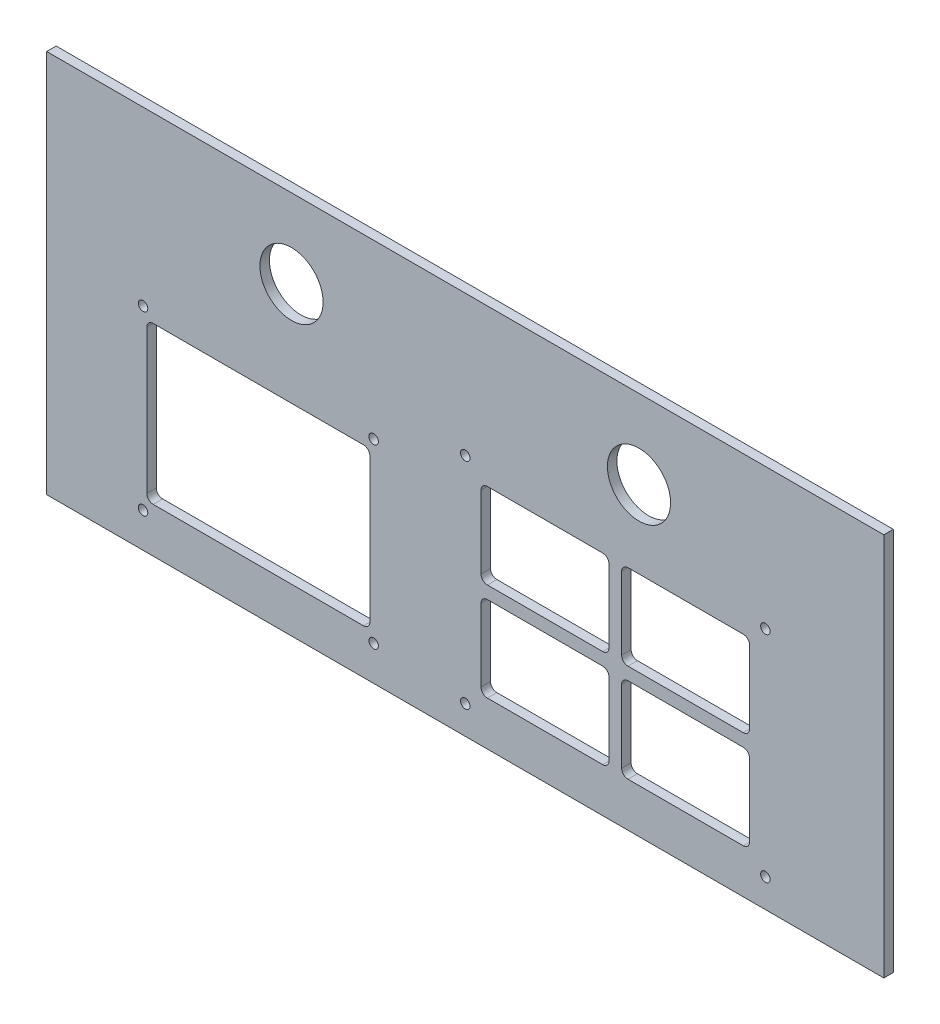
SolidWorks part; units mm, degrees
material "Thornel Mat VMA"
ref_plane "前视基准面" through (0, 0, 0) normal (0, 0, 1) x (1, 0, 0)
ref_plane "上视基准面" through (0, 0, 0) normal (0, 1, 0) x (1, 0, 0)
ref_plane "右视基准面" through (0, 0, 0) normal (1, 0, 0) x (0, 0, -1)
sketch "草图1" plane through (0, 0, 0) normal (0, 0, 1) x (1, 0, 0)
  line L1 (-132.5, -60.75) -> (132.5, -60.75)
  line L2 (-132.5, -60.75) -> (-132.5, 60.75)
  line L3 (-132.5, 60.75) -> (132.5, 60.75)
  line L4 (132.5, -60.75) -> (132.5, 60.75)
  line L5 (0, 60.75) -> (0, -60.75) construction
  line L6 (-132.5, 0) -> (132.5, 0) construction
  point P0 (0, 0)
  dimension "D1" = 265
  dimension "D2" = 121.5
extrude "凸台-拉伸1" add sketch "草图1" along normal blind 3
sketch "草图2" plane through (0, 0, 0) normal (0, 0, -1) x (-1, 0, 0)
  line L0 (50, 40.75) -> (60, 30.75) construction
  line L4 (60, 40.75) -> (50, 40.75)
  line L5 (50, 40.75) -> (50, 30.75)
  line L6 (50, 30.75) -> (60, 30.75)
  line L7 (60, 30.75) -> (60, 40.75)
  line L8 (60, 40.75) -> (50, 40.75) construction
  line L9 (50, 40.75) -> (50, 30.75) construction
  line L10 (50, 30.75) -> (60, 30.75) construction
  line L11 (60, 30.75) -> (60, 40.75) construction
  circle A0 centre (55, 35.75) radius 10
  dimension "D2" = 20
  dimension "D1" = 0
extrude "切除-拉伸1" cut sketch "草图2" against normal blind 10
mirror "镜向1" about plane through (0, 0, 0) normal (1, 0, 0) of "切除-拉伸1"
sketch "草图3" plane through (0, 0, 3) normal (0, 0, 1) x (1, 0, 0)
  line L0 (-97, -0.75) -> (-34, -42.75) construction
  line L2 (-100.8, -46.55) -> (-30.2, -46.55)
  line L3 (-100.8, -46.55) -> (-100.8, 3.05)
  line L4 (-100.8, 3.05) -> (-30.2, 3.05)
  line L5 (-30.2, -46.55) -> (-30.2, 3.05)
  line L6 (-65.5, 3.05) -> (-65.5, -46.55) construction
  line L7 (-100.8, -21.75) -> (-30.2, -21.75) construction
  line L40 (-97, -45.55) -> (-34, -45.55)
  line L41 (-31.2, -42.75) -> (-31.2, -37.25)
  line L42 (-31.2, -37.25) -> (-98, -37.25)
  line L43 (-98, -37.25) -> (-98, -36.25)
  line L44 (-98, -36.25) -> (-31.2, -36.25)
  line L45 (-31.2, -36.25) -> (-31.2, -34.25)
  line L46 (-31.2, -34.25) -> (-98, -34.25)
  line L47 (-98, -34.25) -> (-98, -33.25)
  line L48 (-98, -33.25) -> (-31.2, -33.25)
  line L49 (-31.2, -33.25) -> (-31.2, -28.25)
  line L50 (-31.2, -28.25) -> (-98, -28.25)
  line L51 (-98, -28.25) -> (-98, -27.25)
  line L52 (-98, -27.25) -> (-31.2, -27.25)
  line L53 (-31.2, -27.25) -> (-31.2, -25.25)
  line L54 (-31.2, -25.25) -> (-98, -25.25)
  line L55 (-98, -25.25) -> (-98, -24.25)
  line L56 (-98, -24.25) -> (-31.2, -24.25)
  line L57 (-31.2, -24.25) -> (-31.2, -22.25)
  line L58 (-31.2, -22.25) -> (-94.7, -22.25)
  line L59 (-94.7, -22.25) -> (-94.7, -21.25)
  line L60 (-94.7, -21.25) -> (-31.2, -21.25)
  line L61 (-31.2, -21.25) -> (-31.2, -19.25)
  line L62 (-31.2, -19.25) -> (-98, -19.25)
  line L63 (-98, -19.25) -> (-98, -18.25)
  line L64 (-98, -18.25) -> (-31.2, -18.25)
  line L65 (-31.2, -18.25) -> (-31.2, -16.25)
  line L66 (-31.2, -16.25) -> (-98, -16.25)
  line L67 (-98, -16.25) -> (-98, -15.25)
  line L68 (-98, -15.25) -> (-31.2, -15.25)
  line L69 (-31.2, -15.25) -> (-31.2, -10.25)
  line L70 (-31.2, -10.25) -> (-98, -10.25)
  line L71 (-98, -10.25) -> (-98, -9.25)
  line L72 (-98, -9.25) -> (-31.2, -9.25)
  line L73 (-31.2, -9.25) -> (-31.2, -7.25)
  line L74 (-31.2, -7.25) -> (-98, -7.25)
  line L75 (-98, -7.25) -> (-98, -6.25)
  line L76 (-98, -6.25) -> (-31.2, -6.25)
  line L77 (-31.2, -6.25) -> (-31.2, -0.75)
  line L78 (-34, 2.05) -> (-97, 2.05)
  line L79 (-99.8, -0.75) -> (-99.8, -42.75)
  line L80 (-97, -45.55) -> (-34, -45.55) construction
  line L81 (-31.2, -42.75) -> (-31.2, -37.25) construction
  line L83 (-98, -37.25) -> (-98, -36.25) construction
  line L85 (-31.2, -36.25) -> (-31.2, -34.25) construction
  line L87 (-98, -34.25) -> (-98, -33.25) construction
  line L89 (-31.2, -33.25) -> (-31.2, -28.25) construction
  line L91 (-98, -28.25) -> (-98, -27.25) construction
  line L93 (-31.2, -27.25) -> (-31.2, -25.25) construction
  line L95 (-98, -25.25) -> (-98, -24.25) construction
  line L97 (-31.2, -24.25) -> (-31.2, -22.25) construction
  line L99 (-94.7, -22.25) -> (-94.7, -21.25) construction
  line L101 (-31.2, -21.25) -> (-31.2, -19.25) construction
  line L103 (-98, -19.25) -> (-98, -18.25) construction
  line L105 (-31.2, -18.25) -> (-31.2, -16.25) construction
  line L107 (-98, -16.25) -> (-98, -15.25) construction
  line L109 (-31.2, -15.25) -> (-31.2, -10.25) construction
  line L111 (-98, -10.25) -> (-98, -9.25) construction
  line L113 (-31.2, -9.25) -> (-31.2, -7.25) construction
  line L115 (-98, -7.25) -> (-98, -6.25) construction
  line L117 (-31.2, -6.25) -> (-31.2, -0.75) construction
  line L118 (-34, 2.05) -> (-97, 2.05) construction
  line L119 (-99.8, -0.75) -> (-99.8, -42.75) construction
  arc A4 (-99.8, -42.75) -> (-97, -45.55) centre (-97, -42.75) ccw
  arc A5 (-34, -45.55) -> (-31.2, -42.75) centre (-34, -42.75) ccw
  arc A6 (-31.2, -0.75) -> (-34, 2.05) centre (-34, -0.75) ccw
  arc A7 (-97, 2.05) -> (-99.8, -0.75) centre (-97, -0.75) ccw
  arc A8 (-99.8, -42.75) -> (-97, -45.55) centre (-97, -42.75) ccw construction
  arc A9 (-34, -45.55) -> (-31.2, -42.75) centre (-34, -42.75) ccw construction
  arc A10 (-31.2, -0.75) -> (-34, 2.05) centre (-34, -0.75) ccw construction
  arc A11 (-97, 2.05) -> (-99.8, -0.75) centre (-97, -0.75) ccw construction
  point P0 (-65.5, -21.75)
  dimension "D2" = 1
  dimension "D3" = 1
  dimension "D1" = 0
extrude "切除-拉伸2" cut sketch "草图3" against normal up to surface (3 mm away) up to face at (65, 35.75, 0)
fillet "圆角1" radius 2 4 edges at (-30.2, 3.05, 1.5) (-100.8, 3.05, 1.5) (-100.8, -46.55, 1.5) (-30.2, -46.55, 1.5)
sketch "草图4" plane through (0, 0, 3) normal (0, 0, 1) x (1, 0, 0)
  circle A0 centre (-29, -49.75) radius 1.4986 construction
  circle A1 centre (-29, 6.25) radius 1.4986 construction
  circle A2 centre (-102, -49.75) radius 1.4986 construction
  circle A3 centre (-102, 6.25) radius 1.4986 construction
  circle A4 centre (-29, -49.75) radius 1.4986
  circle A5 centre (-29, 6.25) radius 1.4986
  circle A6 centre (-102, -49.75) radius 1.4986
  circle A7 centre (-102, 6.25) radius 1.4986
extrude "切除-拉伸3" cut sketch "草图4" against normal blind 10
sketch "草图5" plane through (0, 0, 3) normal (0, 0, 1) x (1, 0, 0)
  circle A0 centre (95, 16.25) radius 1.5 construction
  circle A1 centre (95, -51.75) radius 1.5 construction
  circle A2 centre (0, -51.75) radius 1.5 construction
  circle A3 centre (0, 16.25) radius 1.5 construction
  circle A4 centre (95, 16.25) radius 1.5
  circle A5 centre (95, -51.75) radius 1.5
  circle A6 centre (0, -51.75) radius 1.5
  circle A7 centre (0, 16.25) radius 1.5
extrude "切除-拉伸4" cut sketch "草图5" against normal blind 42
sketch "草图6" plane through (0, 0, 3) normal (0, 0, 1) x (1, 0, 0)
  line L0 (0, 16.25) -> (95, -51.75) construction
  line L1 (5, -46.75) -> (90, -46.75)
  line L2 (5, -46.75) -> (5, 11.25)
  line L3 (5, 11.25) -> (90, 11.25)
  line L4 (90, -46.75) -> (90, 11.25)
  line L5 (47.5, 11.25) -> (47.5, -46.75) construction
  line L6 (5, -17.75) -> (90, -17.75) construction
  line L7 (5, -19.75) -> (90, -19.75)
  line L8 (45.5, 11.25) -> (45.5, -46.75)
  line L9 (5, -15.75) -> (90, -15.75)
  line L10 (49.5, 11.25) -> (49.5, -46.75)
  circle A0 centre (95, 16.25) radius 1.5 construction
  point P0 (47.5, -17.75)
  dimension "D1" = 5
  dimension "D2" = 5
  dimension "D3" = 2
  dimension "D4" = 2
extrude "切除-拉伸5" cut sketch "草图6" against normal blind 22 contours L8 L7 L2 L1 | L2 L9 L8 L3 | L3 L10 L9 L4 | L7 L10 L1 L4
fillet "圆角2" radius 2 16 edges at (90, -46.75, 1.5) (49.5, -46.75, 1.5) (49.5, -19.75, 1.5) (90, -19.75, 1.5) (90, -15.75, 1.5) (49.5, -15.75, 1.5) (49.5, 11.25, 1.5) (90, 11.25, 1.5) (45.5, 11.25, 1.5) (45.5, -15.75, 1.5) (5, -46.75, 1.5) (5, -19.75, 1.5) (45.5, -19.75, 1.5) (45.5, -46.75, 1.5) (5, -15.75, 1.5) (5, 11.25, 1.5)
